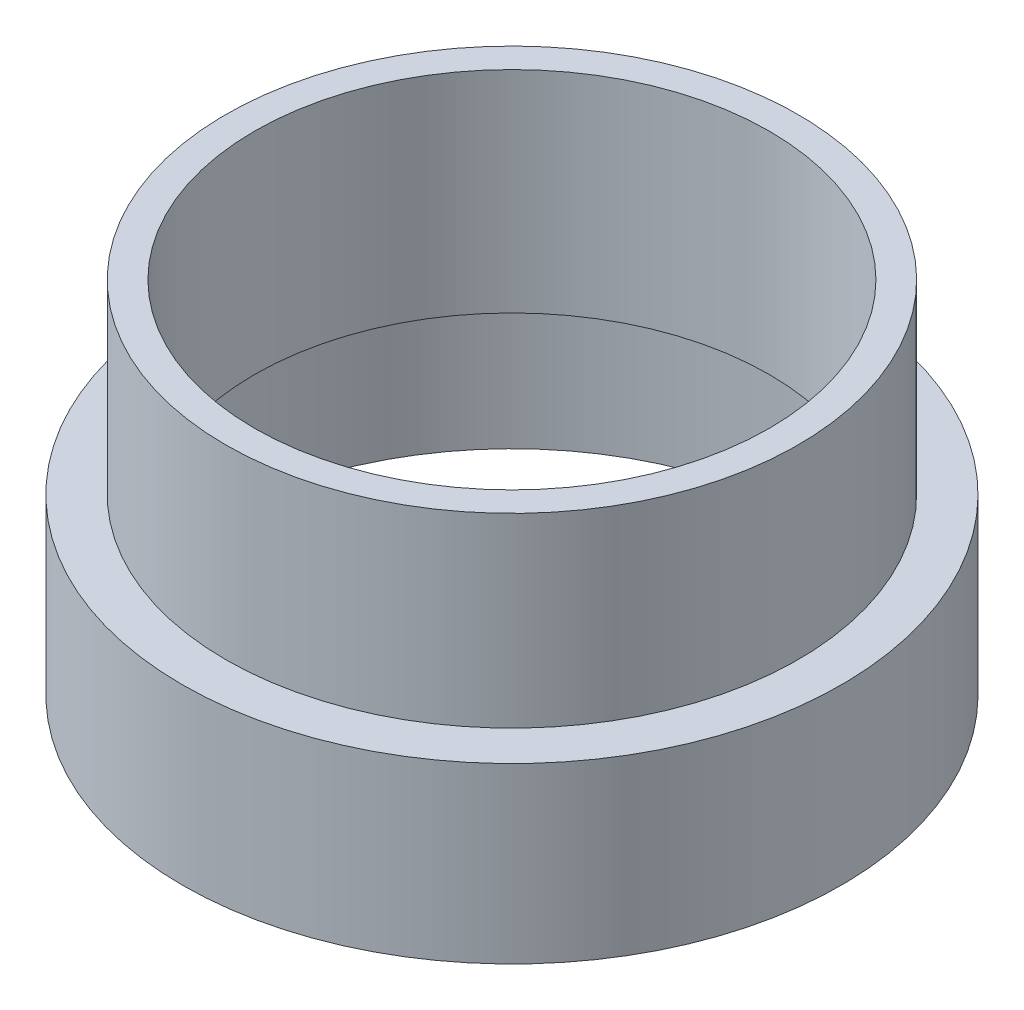
SolidWorks part; units mm, degrees
ref_plane "Front Plane" through (0, 0, 0) normal (0, 0, 1) x (1, 0, 0)
ref_plane "Top Plane" through (0, 0, 0) normal (0, 1, 0) x (1, 0, 0)
ref_plane "Right Plane" through (0, 0, 0) normal (1, 0, 0) x (0, 0, -1)
sketch "Sketch1" plane through (0, 0, 0) normal (0, 1, 0) x (1, 0, 0)
  circle A0 centre (0, 0) radius 13.29
  dimension "D1" = 26.58
extrude "Boss-Extrude1" add sketch "Sketch1" along normal blind 7
sketch "Sketch2" plane through (0, 7, 0) normal (0, 1, 0) x (1, 0, 0)
  circle A0 centre (0, 0) radius 11.54
  dimension "D1" = 23.08
extrude "Boss-Extrude2" add sketch "Sketch2" along normal blind 7.5
sketch "Sketch3" plane through (0, 0, 0) normal (0, -1, 0) x (-1, 0, 0)
  circle A0 centre (0, 0) radius 12.16
  dimension "D1" = 24.32
extrude "Cut-Extrude2" cut sketch "Sketch3" against normal blind 6
sketch "Sketch4" plane through (0, 14.5, 0) normal (0, 1, 0) x (1, 0, 0)
  circle A0 centre (0, 0) radius 10.38
  dimension "D1" = 20.76
extrude "Cut-Extrude4" cut sketch "Sketch4" against normal blind 9
